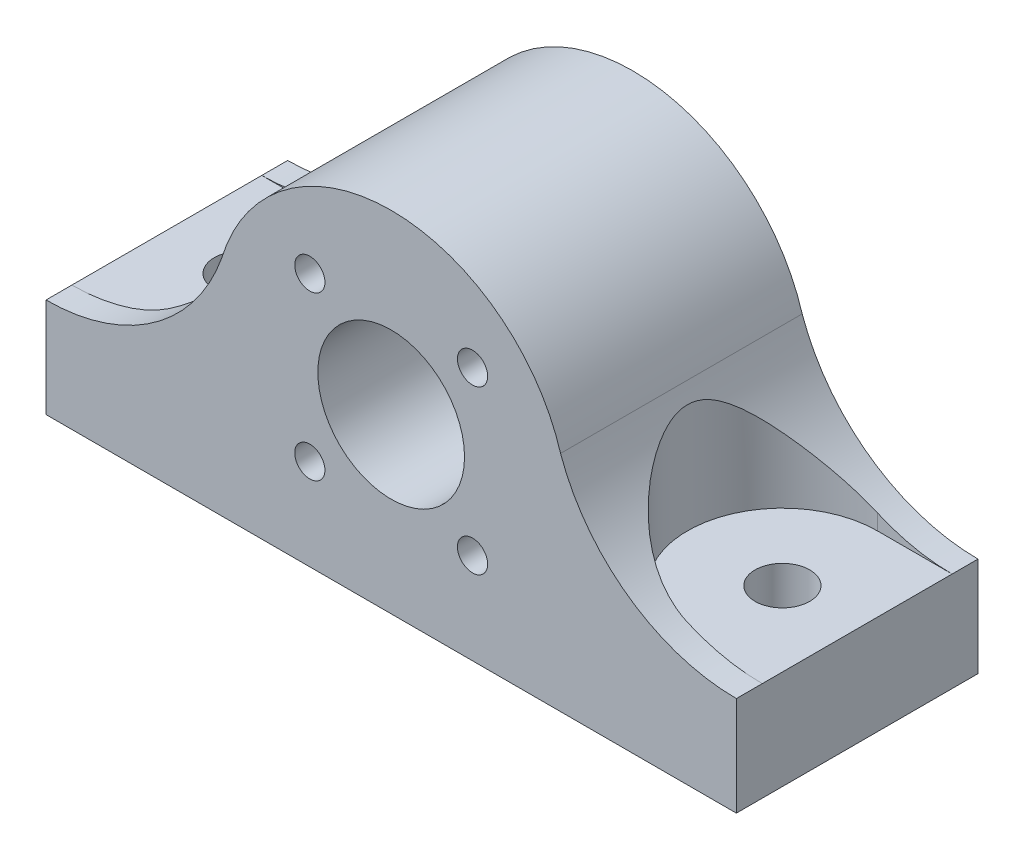
SolidWorks part; units mm, degrees
ref_plane "Alzado" through (0, 0, 0) normal (0, 0, 1) x (1, 0, 0)
ref_plane "Planta" through (0, 0, 0) normal (0, 1, 0) x (1, 0, 0)
ref_plane "Vista lateral" through (0, 0, 0) normal (1, 0, 0) x (0, 0, -1)
sketch "Croquis2" plane through (0, 0, 0) normal (0, 0, 1) x (1, 0, 0)
  line L0 (-24, 17.4) -> (24, 17.4) construction
  line L1 (24, 0) -> (-24, 0) construction
  line L2 (24, 0) -> (24, -6.9)
  line L3 (24, -6.9) -> (-24, -6.9)
  line L4 (-24, 0) -> (-24, -6.9)
  arc A0 (-11.7766, 8.65) -> (11.7766, 8.65) centre (0, 5.1) cw
  arc A1 (-24, 0) -> (-11.7766, 8.65) centre (-24, 12.9616) ccw
  arc A2 (24, 0) -> (11.7766, 8.65) centre (24, 12.9616) cw
  circle A3 centre (0, 5.1) radius 5.1
  dimension "D3" = 24.3
  dimension "D4" = 10.2
  dimension "D1" = 48
  dimension "D2" = 6.9
  dimension "D5" = 8.65
extrude "Saliente-Extruir1" add sketch "Croquis2" along normal blind 16.8
sketch "Croquis3" plane through (0, 0, 16.8) normal (0, 0, 1) x (1, 0, 0)
  line L3 (5.6569, -0.5569) -> (-5.6569, -0.5569) construction
  line L4 (5.6569, -0.5569) -> (5.6569, 10.7569) construction
  line L5 (5.6569, 10.7569) -> (-5.6569, 10.7569) construction
  line L6 (-5.6569, -0.5569) -> (-5.6569, 10.7569) construction
  line L7 (5.6569, -0.5569) -> (-5.6569, 10.7569) construction
  line L8 (5.6569, 10.7569) -> (-5.6569, -0.5569) construction
  circle A2 centre (5.6569, 10.7569) radius 1.05
  circle A3 centre (5.6569, -0.5569) radius 1.05
  circle A4 centre (-5.6569, -0.5569) radius 1.05
  circle A5 centre (-5.6569, 10.7569) radius 1.05
  circle A6 centre (0, 5.1) radius 5.1 construction
  dimension "D1" = 10.2
  dimension "D2" = 2.1
  dimension "D3" = 16
extrude "Cortar-Extruir1" cut sketch "Croquis3" against normal through all
sketch "Croquis4" plane through (0, 0, 0) normal (0, 1, 0) x (1, 0, 0)
  line L0 (-24, -1.8) -> (-24, -15)
  line L1 (-24, -16.8) -> (-24, 0) construction
  line L2 (-24, -15) -> (-18.8, -15)
  line L3 (-24, -1.8) -> (-18.8, -1.8)
  line L4 (-11.7766, 0) -> (-24, 0) construction
  line L5 (-24, -16.8) -> (-11.7766, -16.8) construction
  line L6 (0, 0) -> (0, -16.8) construction
  line L7 (-11.7766, -16.8) -> (11.7766, -16.8) construction
  line L8 (24, -15) -> (18.8, -15)
  line L9 (24, -1.8) -> (24, -15)
  line L10 (24, -1.8) -> (18.8, -1.8)
  arc A0 (-18.8, -1.8) -> (-18.8, -15) centre (-18.8, -8.4) cw
  arc A1 (18.8, -1.8) -> (18.8, -15) centre (18.8, -8.4) ccw
  dimension "D1" = 1.8
  dimension "D2" = 1.8
  dimension "D3" = 5.2
extrude "Cortar-Extruir2" cut sketch "Croquis4" along normal through all
sketch "Croquis5" plane through (0, 0, 0) normal (0, 1, 0) x (1, 0, 0)
  line L2 (-11.7766, 0) -> (-24, 0) construction
  line L3 (-24, -1.8) -> (-24, -15) construction
  line L4 (0, 0) -> (0, -16.8) construction
  line L5 (-11.7766, -16.8) -> (11.7766, -16.8) construction
  circle A0 centre (-18.8, -8.4) radius 1.9
  circle A1 centre (18.8, -8.4) radius 1.9
  dimension "D1" = 3.8
  dimension "D2" = 8.4
  dimension "D3" = 5.2
extrude "Cortar-Extruir3" cut sketch "Croquis5" against normal through all
